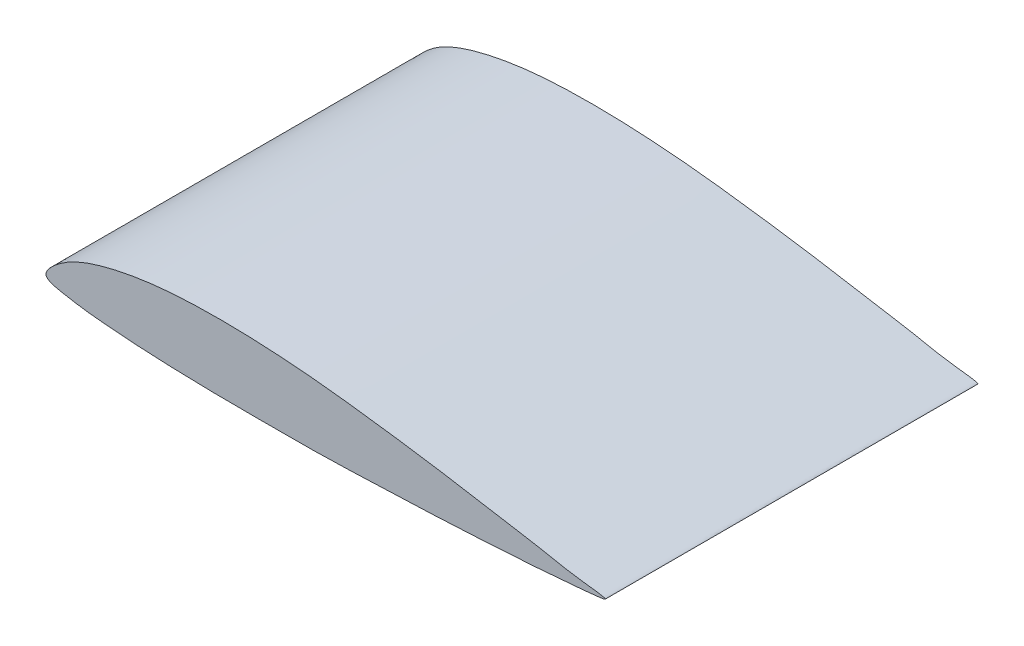
SolidWorks part; units mm, degrees
ref_plane "Спереди"
ref_plane "Сверху" through (0, 0, 0) normal (0, 1, 0) x (1, 0, 0)
ref_plane "Справа" through (0, 0, 0) normal (1, 0, 0) x (0, 0, -1)
curve "Кривая1"
  spline degree 3 poles (0.9423, 0.0078, 0) (1.0288, -0.0001, 0) (0.9427, -0.0071, 0) (0.8877, -0.0122, 0) (0.7986, -0.0179, 0) (0.7004, -0.0234, 0) (0.5999, -0.027, 0) (0.5001, -0.0313, 0) (0.4, -0.0313, 0) (0.3, -0.0313, 0) (0.2166, -0.0289, 0) (0.15, -0.0253, 0) (0.1082, -0.0219, 0) (0.0751, -0.0189, 0) (0.0494, -0.015, 0) (0.0263, -0.0111, 0) (-0.0153, -0.0012, 0) (0.0238, 0.0331, 0) (0.0485, 0.0472, 0) (0.0748, 0.058, 0) (0.1078, 0.068, 0) (0.1497, 0.0772, 0) (0.2163, 0.0864, 0) (0.3, 0.0897, 0) (0.4001, 0.0869, 0) (0.5003, 0.0786, 0) (0.6, 0.0658, 0) (0.7006, 0.0516, 0) (0.7985, 0.0342, 0) (0.8878, 0.0202, 0) (0.9423, 0.0078, 0) (1.0288, -0.0001, 0) (0.9427, -0.0071, 0) knots -0.099674 -0.049826 -0.024872 0 0.024772 0.049422 0.098654 0.147845 0.197003 0.246151 0.295271 0.344391 0.39353 0.418128 0.442766 0.455107 0.467513 0.47999 0.493309 0.513371 0.527691 0.540973 0.553836 0.579004 0.603803 0.652983 0.702118 0.751398 0.800887 0.850519 0.900326 0.950174 0.975128 1 1.024772 1.049422 1.098654 periodic
sketch "Эскиз1" plane through (0, 0, 0) normal (0, 0, 1) x (1, 0, 0)
  spline S1 degree 3 poles (141.402, -1.0665) (154.3149, -0.0217) (141.3456, 1.1669) (133.1699, 3.0314) (119.7779, 5.1266) (105.09, 7.7427) (90.003, 9.8704) (75.0385, 11.7968) (60.0204, 13.0336) (44.9994, 13.4614) (32.45, 12.9597) (22.4506, 11.5842) (16.176, 10.2054) (11.2144, 8.6931) (7.2713, 7.0822) (3.5769, 4.9713) (-2.2957, -0.1854) (3.9472, -1.6652) (7.4158, -2.2458) (11.2585, -2.8299) (16.2356, -3.2795) (22.497, -3.8014) (32.4917, -4.3417) (44.9985, -4.6879) (59.9983, -4.6955) (75.0096, -4.7001) (89.9849, -4.0438) (105.0637, -3.5142) (119.7884, -2.688) (133.148, -1.8326) (141.402, -1.0665) (154.3149, -0.0217) (141.3456, 1.1669) knots -0.098654 -0.049422 -0.024772 0 0.024872 0.049826 0.099674 0.149481 0.199113 0.248602 0.297882 0.347017 0.396197 0.420996 0.446164 0.459027 0.472309 0.486629 0.506691 0.52001 0.532487 0.544893 0.557234 0.581872 0.60647 0.655609 0.704729 0.753849 0.802997 0.852155 0.901346 0.950578 0.975228 1 1.024872 1.049826 1.099674 only from (150, 0) to (150, 0)
extrude "Бобышка-Вытянуть1" add sketch "Эскиз1" along normal blind 100
